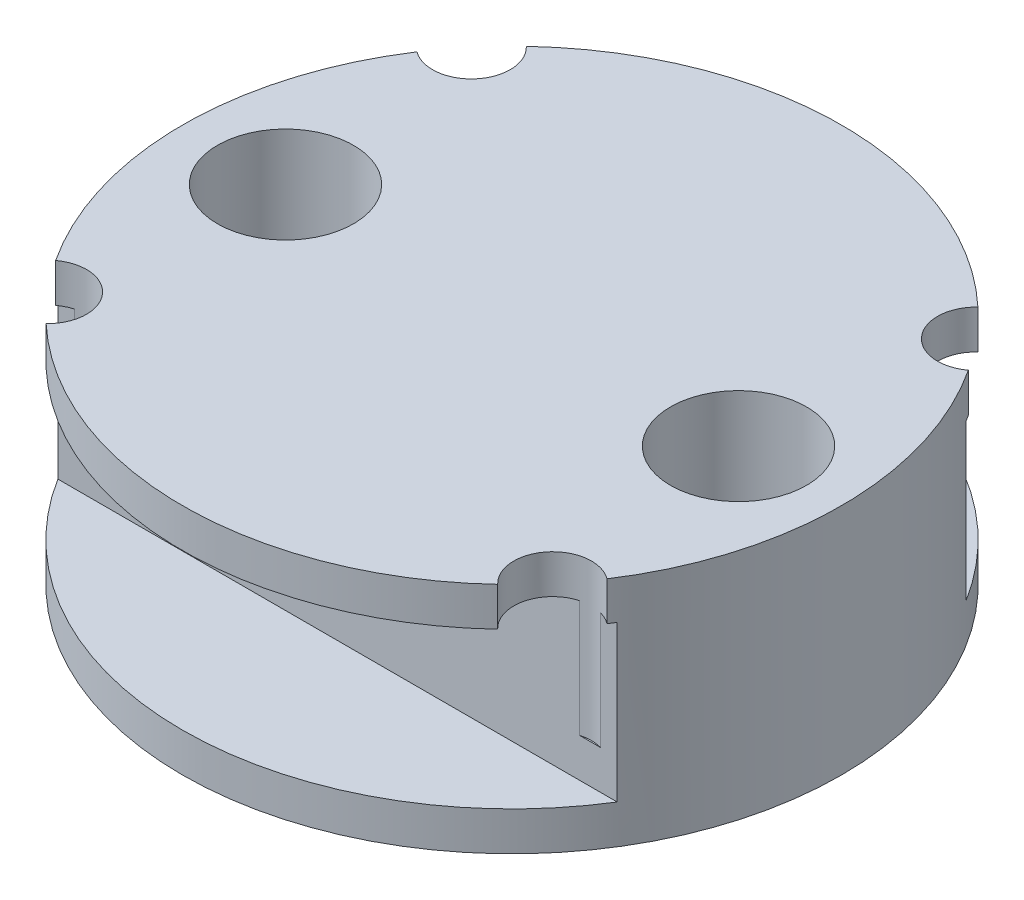
SolidWorks part; units mm, degrees
material "Copper"
ref_plane "Front Plane" through (0, 0, 0) normal (0, 0, 1) x (1, 0, 0)
ref_plane "Top Plane" through (0, 0, 0) normal (0, 1, 0) x (1, 0, 0)
ref_plane "Right Plane" through (0, 0, 0) normal (1, 0, 0) x (0, 0, -1)
sketch "Sketch1" plane through (0, 0, 0) normal (0, 1, 0) x (1, 0, 0)
  circle A3 centre (-4.6079, 9.9677) radius 8.4778
  circle A4 centre (-4.6079, 9.9677) radius 8.4778
  dimension "D2" = 1
extrude "Boss-Extrude1" add sketch "Sketch1" against normal blind 6
sketch "Sketch2" plane through (0, 0, 0) normal (0, 1, 0) x (1, 0, 0)
  circle A0 centre (-10.4343, 9.9677) radius 1.75 construction
  circle A1 centre (1.2185, 9.9677) radius 1.75 construction
  circle A2 centre (-10.4343, 9.9677) radius 1.75
  circle A3 centre (1.2185, 9.9677) radius 1.75
extrude "Cut-Extrude1" cut sketch "Sketch2" against normal blind 3
hole_wizard "CBORE for M5 Hex Head Bolt1" positions "Sketch7" profile "Sketch6" counterbore size "M5" standard "ANSI Metric" end condition through all
sketch "Sketch7" plane through (0, -6, 0) normal (0, -1, 0) x (-1, 0, 0)
  point P0 (10.4343, 9.9677)
  point P3 (-1.2185, 9.9677)
sketch "Sketch6" plane through (-10.4343, -6, -9.9677) normal (1, 0, 0) x (0, 0, -1)
  line L0 (0, 0) -> (0, 6)
  line L1 (0, 6) -> (0.75, 6)
  line L3 (0.75, 6) -> (0.75, 1)
  line L4 (0.75, 1) -> (2, 1)
  line L5 (2, 1) -> (2, 0)
  line L7 (2, 0) -> (0, 0)
  line L11 (0, -6.35) -> (0, 107.95) construction
  dimension "Thru Hole Dia." = 1.5
  dimension "Thru Hole Depth" = 6
  dimension "C'Bore Dia." = 4
  dimension "C'Bore Depth" = 1
sketch "Sketch9" plane through (-5.3455, 57.8722, -9.9293) normal (0, 1, 0) x (1, 0, 0)
  line L0 (0.7377, -8.4395) -> (0.7377, -4.4395)
  circle A0 centre (0.7377, 0.0383) radius 8.4778 construction
  dimension "D1" = 4
sketch "Sketch10" plane through (0, 0, 0) normal (0, 0, 1) x (1, 0, 0)
  line L0 (3.8699, 0) -> (-13.0856, 0) construction
  line L1 (-15.0747, -1) -> (6.3804, -1)
  line L2 (-15.0747, -1) -> (-15.0747, -5)
  line L3 (-15.0747, -5) -> (6.3804, -5)
  line L4 (6.3804, -1) -> (6.3804, -5)
  line L5 (-13.0856, -6) -> (3.8699, -6) construction
  dimension "D1" = 1
  dimension "D2" = 1
extrude "Cut-Extrude6" cut sketch "Sketch10" against normal blind 4 from offset 1.48 contours L3 L4 L1 L2 offset against normal yes
sketch3d "3DSketch3" [suppressed]
  line L1 (-16.7808, -0.9511, -1.4899) -> (8.261, -0.9511, -1.4899)
  line L2 (-16.7808, -0.9511, -1.4899) -> (-16.7808, -5.2702, -1.4899)
  line L3 (-16.7808, -5.2702, -1.4899) -> (8.261, -5.2702, -1.4899)
  line L4 (8.261, -0.9511, -1.4899) -> (8.261, -5.2702, -1.4899)
ref_plane "Plane2" through (0, 0, -18.4455) normal (0, 0, -1) x (-1, 0, 0)
sketch "Sketch12" plane through (0, 0, -18.4455) normal (0, 0, -1) x (-1, 0, 0)
  line L0 (-3.8699, -6) -> (13.0856, -6) construction
  line L1 (15.2975, -5) -> (-7.0394, -5)
  line L2 (15.2975, -5) -> (15.2975, -1)
  line L3 (15.2975, -1) -> (-7.0394, -1)
  line L4 (-7.0394, -5) -> (-7.0394, -1)
  line L5 (13.0856, 0) -> (-3.8699, 0) construction
  dimension "D1" = 1
  dimension "D2" = 1
extrude "Cut-Extrude7" cut sketch "Sketch12" against normal blind 4
sketch "Sketch13" plane through (0, 0, 0) normal (0, 1, 0) x (1, 0, 0)
  line L0 (-4.6079, 18.4455) -> (-4.6079, -0.8333) construction
  line L1 (3.3, 18.4455) -> (-3.3, 18.4455) construction
  line L2 (-13.0856, 9.9677) -> (3.8699, 9.9677) construction
  circle A0 centre (1.8865, 4.5183) radius 1
  circle A1 centre (-4.6079, 9.9677) radius 8.4778 construction
  circle A2 centre (-11.1022, 4.5183) radius 1
  circle A3 centre (-11.1022, 15.4171) radius 1
  circle A4 centre (1.8865, 15.4171) radius 1
  dimension "D1" = 2
extrude "Cut-Extrude8" cut sketch "Sketch13" against normal blind 4 contours A2 | A0 | A3 | A4
